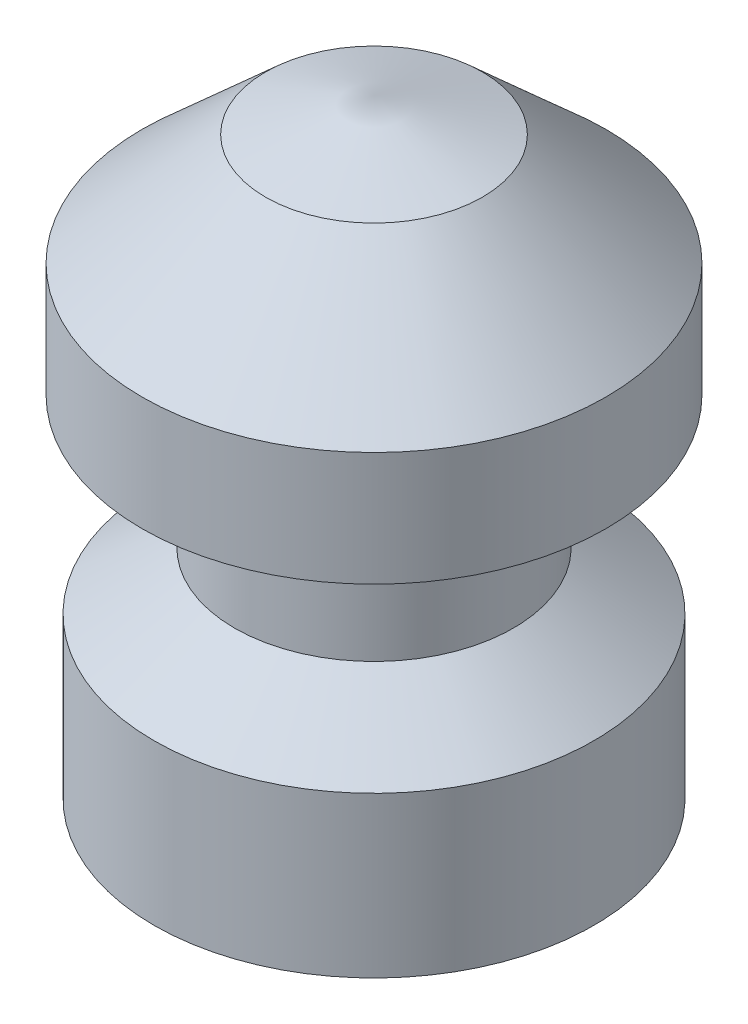
SolidWorks part; units mm, degrees
ref_plane "정면" through (0, 0, 0) normal (0, 0, 1) x (1, 0, 0)
ref_plane "윗면" through (0, 0, 0) normal (0, 1, 0) x (1, 0, 0)
ref_plane "우측면" through (0, 0, 0) normal (1, 0, 0) x (0, 0, -1)
sketch "스케치1" plane through (0, 0, 0) normal (1, 0, 0) x (0, 0, -1)
  line L0 (0, 0) -> (0.4957, 0)
  line L1 (0.4957, 0) -> (1.75, -1.613)
  line L2 (1.75, -1.613) -> (2.75, -1.613)
  line L3 (2.75, -1.613) -> (2.75, 0.387)
  line L4 (2.75, 0.387) -> (1.7434, 1.103)
  line L6 (0, 0) -> (0, 6)
  line L7 (1.3564, 5.5767) -> (0, 6)
  line L8 (0, 6) -> (0, 0) construction
  line L9 (2.9, 2.7579) -> (2.9, 4.1839)
  line L10 (2.9, 4.1839) -> (1.3564, 5.5767)
  line L11 (1.7434, 1.103) -> (1.7434, 2.103)
  line L12 (1.7434, 2.103) -> (2.9, 2.7579)
  dimension "D1" = 5.8
  dimension "D2" = 5.5
  dimension "D3" = 6
  dimension "D4" = 2
  dimension "D5" = 1
  dimension "D6" = 1
revolve "회전1" add sketch "스케치1" angle 360 about L8
